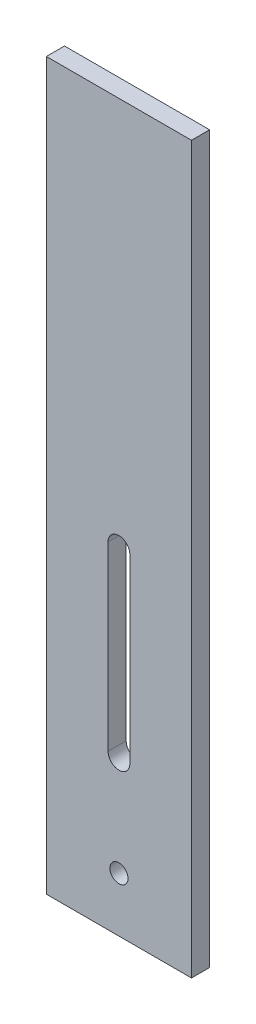
SolidWorks part; units mm, degrees
ref_plane "Front Plane" through (0, 0, 0) normal (0, 0, 1) x (1, 0, 0)
ref_plane "Top Plane" through (0, 0, 0) normal (0, 1, 0) x (1, 0, 0)
ref_plane "Right Plane" through (0, 0, 0) normal (1, 0, 0) x (0, 0, -1)
sketch "Sketch1" plane through (0, 0, 0) normal (0, 0, 1) x (1, 0, 0)
  line L0 (0, -107.3764) -> (-40, -107.3764) construction
  line L1 (0, 0) -> (-40, 0)
  line L2 (0, 0) -> (0, -200)
  line L3 (0, -200) -> (-40, -200)
  line L4 (-40, 0) -> (-40, -200)
  line L5 (0, -157.3764) -> (-40, -157.3764) construction
  line L6 (-20, -107.3764) -> (-20, -157.3764) construction
  line L7 (-17, -107.3764) -> (-17, -157.3764)
  line L8 (-23, -107.3764) -> (-23, -157.3764)
  line L9 (-40, -185) -> (0, -185) construction
  arc A0 (-17, -107.3764) -> (-23, -107.3764) centre (-20, -107.3764) ccw
  arc A1 (-23, -157.3764) -> (-17, -157.3764) centre (-20, -157.3764) ccw
  circle A2 centre (-20, -185) radius 2.5
  point P11 (-20, -132.3764)
  dimension "D3" = 3
  dimension "D6" = 5
  dimension "D1" = 40
  dimension "D2" = 200
  dimension "D4" = 50
  dimension "D5" = 20
  dimension "D7" = 15
extrude "Boss-Extrude1" add sketch "Sketch1" along normal blind 5
